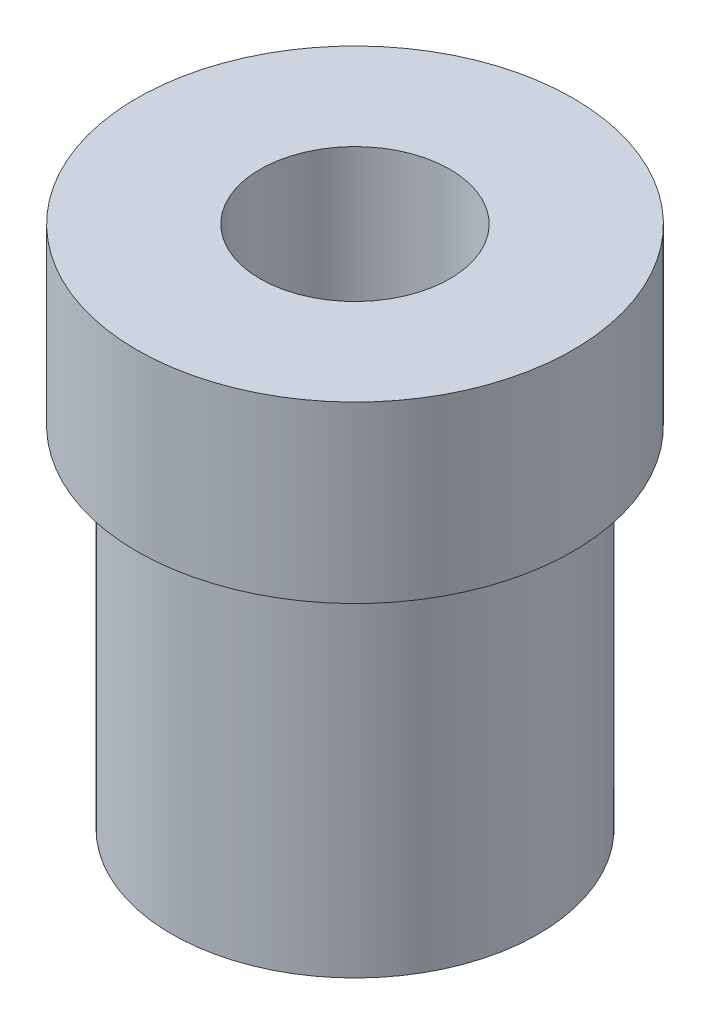
SolidWorks part; units mm, degrees
material "AISI 4130 Steel, annealed at 865C"
ref_plane "Front Plane" through (0, 0, 0) normal (0, 0, 1) x (1, 0, 0)
ref_plane "Top Plane" through (0, 0, 0) normal (0, 1, 0) x (1, 0, 0)
ref_plane "Right Plane" through (0, 0, 0) normal (1, 0, 0) x (0, 0, -1)
sketch "Sketch1" plane through (0, 0, 0) normal (0, 1, 0) x (1, 0, 0)
  circle A0 centre (0, 0) radius 7.9375
  dimension "D1" = 15.875
extrude "Boss-Extrude1" add sketch "Sketch1" along normal blind 6.35
sketch "Sketch2" plane through (0, 0, 0) normal (0, -1, 0) x (1, 0, 0)
  circle A0 centre (0, 0) radius 6.6675
  dimension "D1" = 13.335
extrude "Boss-Extrude2" add sketch "Sketch2" along normal blind 12.7
sketch "Sketch5" plane through (0, 6.35, 0) normal (0, 1, 0) x (1, 0, 0)
  circle A0 centre (0, 0) radius 3.4544
  dimension "D1" = 6.9088
extrude "Cut-Extrude1" cut sketch "Sketch5" against normal through all both and the other way through all
thread "Thread1" pitch 1.0583 start angle 0, offset 0, length 50.8, pitch 1.0583, diameter 6.9088
ref_plane "Plane2" through (-3.4544, 6.35, 0) normal (0, 0, 1) x (-1, 0, 0)
sketch "Thread Profile2" plane through (-3.4544, 6.35, 0) normal (0, 0, 1) x (-1, 0, 0)
  line L0 (0, 0) -> (0, 1.0583) construction
  line L1 (0, 0) -> (0.5728, 0.3307)
  line L2 (0.5728, 0.3307) -> (0.5728, 0.463)
  line L3 (0.5728, 0.463) -> (0, 0.7937)
  line L4 (0.5728, 0.3969) -> (0, 0.3969) construction
  line L11 (0, 0) -> (0, 0.7937)
  point P2 (0, 0)
  dimension "Pitch" = 1.0583
  dimension "Profile_Angle" = 60
  dimension "Profile_Land" = 0.1323
  dimension "Profile_Height" = 0.5728
